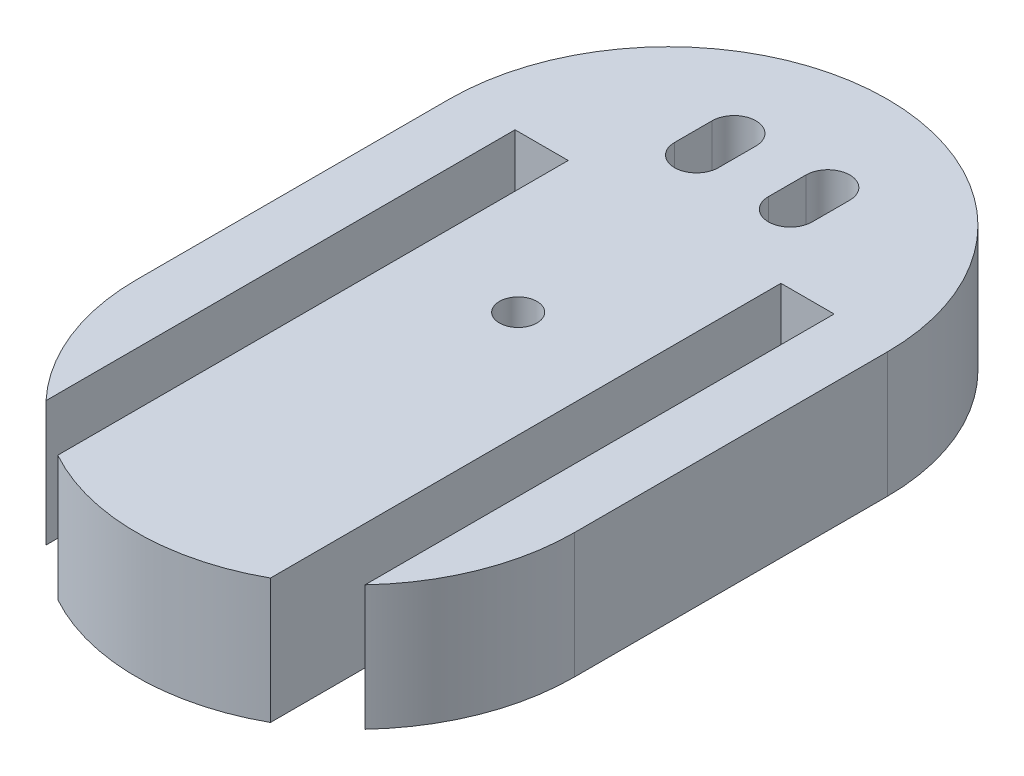
SolidWorks part; units mm, degrees
material "Thornel Mat VMA"
ref_plane "前视基准面" through (0, 0, 0) normal (0, 0, 1) x (1, 0, 0)
ref_plane "上视基准面" through (0, 0, 0) normal (0, 1, 0) x (1, 0, 0)
ref_plane "右视基准面" through (0, 0, 0) normal (1, 0, 0) x (0, 0, -1)
other "Configuration Table"
sketch "草图1" plane through (0, 0, 0) normal (0, 1, 0) x (1, 0, 0)
  line L0 (0, 0) -> (0, -10) construction
  line L1 (7, 0) -> (7, -10)
  line L2 (-7, 0) -> (-7, -10)
  arc A0 (7, 0) -> (-7, 0) centre (0, 0) ccw
  arc A1 (-7, -10) -> (7, -10) centre (0, -10) ccw
  point P3 (0, -5)
  dimension "D1" = 7
  dimension "D2" = 10
extrude "凸台-拉伸1" add sketch "草图1" along normal blind 4
sketch "草图2" plane through (0, 4, 0) normal (0, 1, 0) x (1, 0, 0)
  line L0 (0, -1000) -> (0, 49000) construction
  line L10 (-5.1, 0.2) -> (-3.4, 0.2)
  line L11 (-5.1, 0.2) -> (-5.1, -55.692)
  line L12 (-5.1, -55.692) -> (-3.4, -55.692)
  line L13 (-3.4, 0.2) -> (-3.4, -55.692)
  line L14 (5.1, -55.692) -> (3.4, -55.692)
  line L15 (3.4, 0.2) -> (3.4, -55.692)
  line L16 (5.1, 0.2) -> (3.4, 0.2)
  line L17 (5.1, 0.2) -> (5.1, -55.692)
  arc A1 (7, 0) -> (-7, 0) centre (0, 0) ccw construction
  dimension "D1" = 3.4
  dimension "D2" = 5.1
  dimension "D3" = 0.2
extrude "切除-拉伸1" cut sketch "草图2" against normal through all
sketch "草图3" plane through (0, 4, 0) normal (0, 1, 0) x (1, 0, 0)
  line L0 (-1.5, 2.4) -> (-1.5, 3.6) construction
  line L1 (-2.2, 2.4) -> (-2.2, 3.6)
  line L2 (-0.8, 2.4) -> (-0.8, 3.6)
  line L3 (0, -1000) -> (0, 49000) construction
  line L4 (1.5, 2.4) -> (1.5, 3.6) construction
  line L5 (2.2, 2.4) -> (2.2, 3.6)
  line L6 (0.8, 2.4) -> (0.8, 3.6)
  arc A0 (-2.2, 2.4) -> (-0.8, 2.4) centre (-1.5, 2.4) ccw
  arc A1 (-0.8, 3.6) -> (-2.2, 3.6) centre (-1.5, 3.6) ccw
  arc A2 (2.2, 2.4) -> (0.8, 2.4) centre (1.5, 2.4) cw
  arc A3 (0.8, 3.6) -> (2.2, 3.6) centre (1.5, 3.6) cw
  point P2 (-1.5, 3)
  point P12 (1.5, 3)
  dimension "D1" = 0.7
  dimension "D2" = 1.2
  dimension "D3" = 1.5
  dimension "D4" = 3
extrude "切除-拉伸2" cut sketch "草图3" against normal through all
sketch "草图4" plane through (0, 4, 0) normal (0, 1, 0) x (1, 0, 0)
  line L0 (5.1, 0.2) -> (3.4, 0.2) construction
  circle A1 centre (0, -4.8) radius 0.6
  dimension "D2" = 5
  dimension "D3" = 1.2
extrude "切除-拉伸3" cut sketch "草图4" against normal through all
